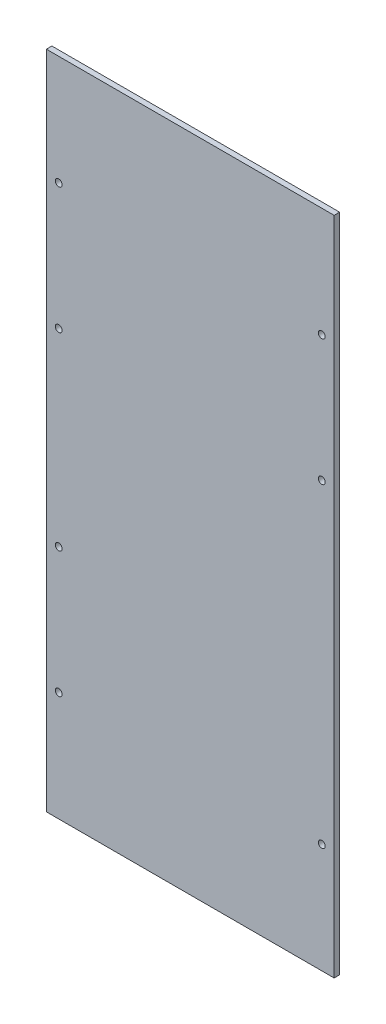
SolidWorks part; units mm, degrees
ref_plane "Alzado" through (0, 0, 0) normal (0, 0, 1) x (1, 0, 0)
ref_plane "Planta" through (0, 0, 0) normal (0, 1, 0) x (1, 0, 0)
ref_plane "Vista lateral" through (0, 0, 0) normal (1, 0, 0) x (0, 0, -1)
sketch "Croquis1" plane through (0, 0, 0) normal (0, 0, 1) x (1, 0, 0)
  line L1 (-90.5016, 703.6284) -> (119.4984, 703.6284)
  line L2 (-90.5016, 703.6284) -> (-90.5016, 1185.6284)
  line L3 (-90.5016, 1185.6284) -> (119.4984, 1185.6284)
  line L4 (119.4984, 703.6284) -> (119.4984, 1185.6284)
  circle A0 centre (110.4984, 1105.6384) radius 2.5
  circle A1 centre (-81.5016, 1105.6384) radius 2.5
  circle A2 centre (-81.5016, 1013.6384) radius 2.5
  circle A3 centre (110.4984, 1013.6384) radius 2.5
  circle A4 centre (-81.5016, 875.6184) radius 2.5
  circle A5 centre (110.4984, 783.6184) radius 2.5
  circle A6 centre (-81.5016, 783.6184) radius 2.5
  dimension "D1" = 210
extrude "Saliente-Extruir1" add sketch "Croquis1" along normal blind 4
